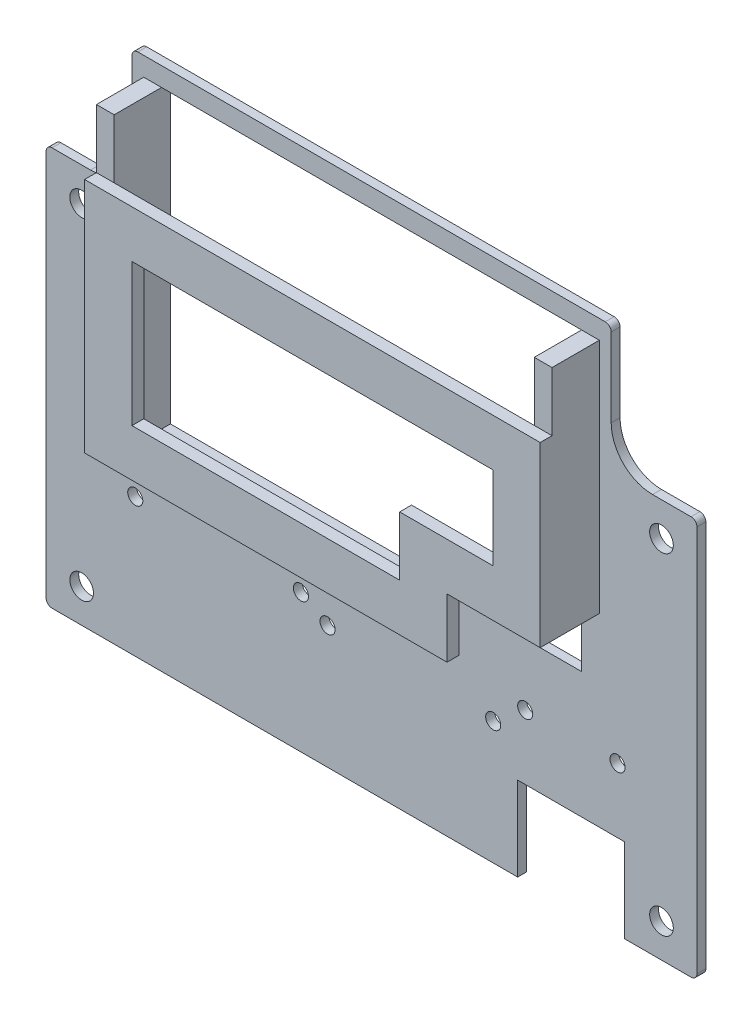
SolidWorks part; units mm, degrees
ref_plane "前基準面" through (0, 0, 0) normal (0, 0, 1) x (1, 0, 0)
ref_plane "上基準面" through (0, 0, 0) normal (0, 1, 0) x (1, 0, 0)
ref_plane "右基準面" through (0, 0, 0) normal (1, 0, 0) x (0, 0, -1)
sketch "草圖1" plane through (0, 0, 0) normal (0, 0, 1) x (1, 0, 0)
  line L5 (-78.5836, -93.3419) -> (16.5192, -93.3419)
  line L36 (9.5192, -18.9462) -> (9.5192, -5.6591)
  line L37 (8.5192, -4.6591) -> (-70.4808, -4.6591)
  line L38 (-71.4808, -5.6591) -> (-71.4808, -18.9462)
  line L39 (-78.4808, -25.9462) -> (-84.9808, -25.9462)
  line L40 (-85.9808, -26.9462) -> (-85.9808, -92.3419)
  line L41 (-84.9834, -93.3419) -> (-78.5836, -93.3419)
  line L45 (16.5192, -93.3419) -> (23.0192, -93.3419)
  line L46 (24.0192, -92.3419) -> (24.0192, -26.9161)
  line L47 (23.0192, -25.9462) -> (16.5192, -25.9462)
  circle A12 centre (-79.9808, -31.644) radius 2
  circle A13 centre (18.0192, -31.644) radius 2
  circle A14 centre (18.0192, -87.644) radius 2
  circle A15 centre (-79.9808, -87.644) radius 2
  arc A36 (9.5192, -18.9462) -> (16.5192, -25.9462) centre (16.5192, -18.9462) ccw
  arc A37 (9.5192, -5.6591) -> (8.5192, -4.6591) centre (8.5192, -5.6591) ccw
  arc A38 (-70.4808, -4.6591) -> (-71.4808, -5.6591) centre (-70.4808, -5.6591) ccw
  arc A39 (-78.4808, -25.9462) -> (-71.4808, -18.9462) centre (-78.4808, -18.9462) ccw
  arc A40 (-84.9808, -25.9462) -> (-85.9808, -26.9462) centre (-84.9808, -26.9462) ccw
  arc A41 (-85.9808, -92.3419) -> (-84.9834, -93.3419) centre (-84.9808, -92.3419) ccw
  arc A46 (23.0192, -93.3419) -> (24.0192, -92.3419) centre (23.0192, -92.3419) ccw
  arc A47 (24.0192, -26.9161) -> (23.0192, -25.9462) centre (23.0196, -26.9462) ccw
  dimension "D2" = 4
  dimension "D3" = 4
  dimension "D4" = 4
  dimension "D5" = 4
extrude "填料-伸長1" add sketch "草圖1" along normal blind 1.5
sketch "草圖2" plane through (0, 0, 1.5) normal (0, 0, 1) x (1, 0, 0)
  line L0 (-71.4808, -5.6591) -> (-71.4808, -18.9462) construction
  line L1 (-69.4808, -7.8571) -> (-66.4808, -7.8571)
  line L2 (-69.4808, -7.8571) -> (-69.4808, -57.8571)
  line L3 (-69.4808, -57.8571) -> (-66.4808, -57.8571)
  line L4 (-66.4808, -7.8571) -> (-66.4808, -57.8571)
  line L5 (4.5192, -7.8571) -> (7.5192, -7.8571)
  line L6 (4.5192, -7.8571) -> (4.5192, -47.8571)
  line L7 (4.5192, -47.8571) -> (7.5192, -47.8571)
  line L8 (7.5192, -7.8571) -> (7.5192, -47.8571)
  line L9 (9.5192, -18.9462) -> (9.5192, -5.6591) construction
  dimension "D1" = 3
  dimension "D2" = 50
  dimension "D3" = 2
  dimension "D4" = 2
  dimension "D5" = 3
  dimension "D6" = 40
extrude "填料-伸長3" add sketch "草圖2" along normal blind 8
sketch "草圖3" plane through (0, 0, 9.5) normal (0, 0, 1) x (1, 0, 0)
  line L0 (-69.4808, -57.8571) -> (-66.4808, -57.8571) construction
  line L1 (-69.4808, -17.828) -> (7.5192, -17.828)
  line L2 (-69.4808, -17.828) -> (-69.4808, -57.8571)
  line L3 (-69.4808, -57.8571) -> (-8.2251, -57.8571)
  line L4 (7.5192, -17.828) -> (7.5192, -47.8571)
  line L6 (7.5192, -47.8571) -> (-8.2251, -47.8571)
  line L9 (-8.2251, -47.8571) -> (-8.2251, -57.8571)
extrude "填料-伸長4" add sketch "草圖3" along normal blind 2
sketch "草圖4" plane through (0, 0, 1.5) normal (0, 0, 1) x (1, 0, 0)
  line L1 (-66.4808, -57.8571) -> (4.5192, -57.8571)
  line L2 (-66.4808, -57.8571) -> (-66.4808, -7.8571)
  line L3 (-66.4808, -7.8571) -> (4.5192, -7.8571)
  line L4 (4.5192, -57.8571) -> (4.5192, -7.8571)
extrude "除料-伸長1" cut sketch "草圖4" against normal through all
sketch "草圖7" plane through (0, 0, 11.5) normal (0, 0, 1) x (1, 0, 0)
  line L6 (-16.2251, -49.8571) -> (-16.2251, -39.8571)
  line L7 (-16.2251, -49.8571) -> (-16.2251, -39.8571)
  line L8 (-61.4808, -25.828) -> (-61.4808, -49.8571)
  line L9 (-61.4808, -49.8571) -> (-16.2251, -49.8571)
  line L10 (-0.4808, -39.8571) -> (-0.4808, -25.828)
  line L11 (-0.4808, -25.828) -> (-61.4808, -25.828)
  line L12 (-61.4808, -25.828) -> (-61.4808, -49.8571)
  line L13 (-61.4808, -49.8571) -> (-16.2251, -49.8571)
  line L14 (-0.4808, -39.8571) -> (-0.4808, -25.828)
  line L15 (-0.4808, -25.828) -> (-61.4808, -25.828)
  line L16 (-16.2251, -39.8571) -> (-0.4808, -39.8571)
  line L17 (-16.2251, -39.8571) -> (-0.4808, -39.8571)
  dimension "D1" = 8
extrude "除料-伸長3" cut sketch "草圖7" against normal through all
hole_wizard "M2.5 螺旋的螺孔鑽1" positions "草圖8" profile "草圖9" hole size "M2.5x0.45" standard "Ansi Metric"
sketch "草圖8" plane through (0, 0, 1.5) normal (0, 0, 1) x (1, 0, 0)
  point P0 (10.5894, -68.2442)
  point P2 (-5.0106, -68.2442)
  point P4 (-10.4197, -72.5712)
  point P6 (-38.4197, -72.5712)
  point P8 (-42.9197, -69.9617)
  point P10 (-70.9197, -69.9617)
  point P14 (-64.1308, -20.2071)
  point P16 (-0.3308, -20.2071)
  point P23 (-64.1308, -20.2071)
  point P25 (-0.3308, -20.2071)
sketch "草圖9" plane through (10.5894, -68.2442, 1.5) normal (1, 0, 0) x (0, -1, 0)
  line L0 (0, 0) -> (0, 1.5)
  line L1 (0, 1.5) -> (1.275, 1.5)
  line L2 (1.275, 1.5) -> (1.275, 0)
  line L5 (1.275, 0) -> (0, 0)
  line L11 (0, -6.35) -> (0, 107.95) construction
  dimension "貫穿孔直徑" = 2.55
  dimension "貫穿孔深度" = 1.5
sketch "草圖11" plane through (0, 0, 1.5) normal (0, 0, 1) x (1, 0, 0)
  line L0 (-84.9834, -93.3419) -> (23.0192, -93.3419) construction
  line L1 (11.7894, -79.1442) -> (-6.2856, -79.1442)
  line L2 (11.7894, -79.1442) -> (11.7894, -93.3419)
  line L3 (11.7894, -93.3419) -> (-6.2856, -93.3419)
  line L4 (-6.2856, -79.1442) -> (-6.2856, -93.3419)
extrude "除料-伸長4" cut sketch "草圖11" against normal through all
